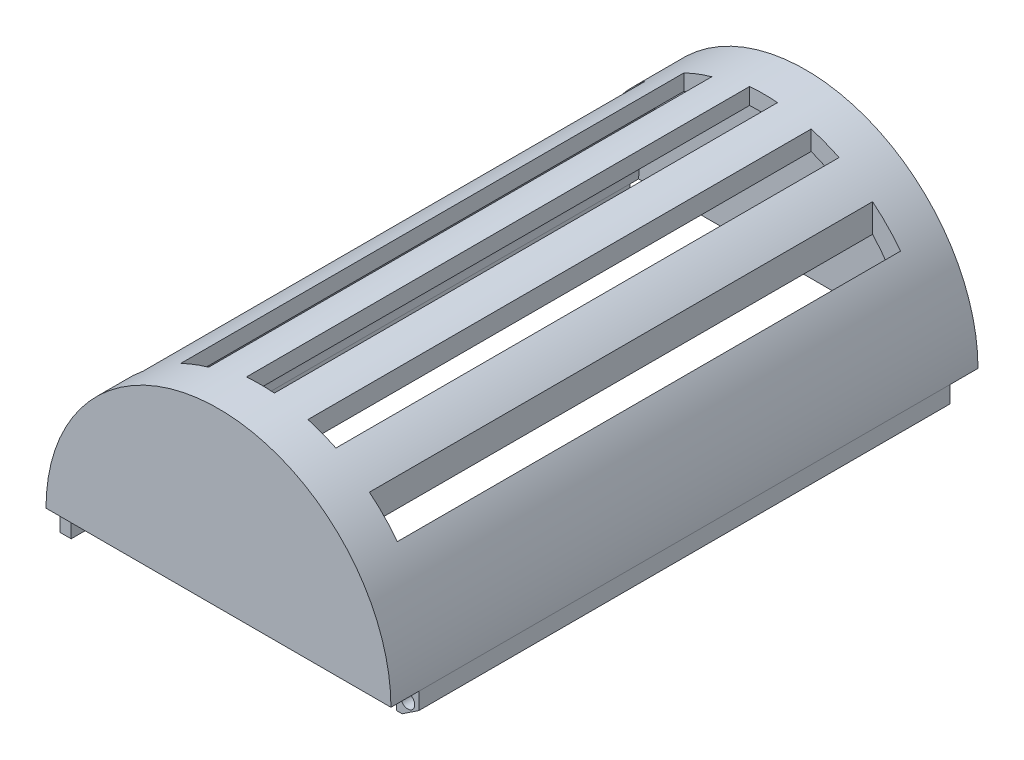
SolidWorks part; units mm, degrees
ref_plane "前基準面" through (0, 0, 0) normal (0, 0, 1) x (1, 0, 0)
ref_plane "上基準面" through (0, 0, 0) normal (0, 1, 0) x (1, 0, 0)
ref_plane "右基準面" through (0, 0, 0) normal (1, 0, 0) x (0, 0, -1)
sketch "草圖1" plane through (0, 0, 0) normal (0, 0, 1) x (1, 0, 0)
  line L0 (-61.7, 0) -> (-57.7, 0) construction
  line L1 (-61.7, 0) -> (-61.7, -10)
  line L2 (-61.7, -10) -> (-57.7, -10)
  line L3 (-57.7, -10) -> (-57.7, 0)
  line L4 (53.7, 0) -> (61.7, 0)
  line L5 (53.7, 0) -> (61.7, 0) construction
  arc A0 (61.7, 0) -> (-61.7, 0) centre (0, 0) ccw
  arc A2 (-57.7, 0) -> (53.7, 0) centre (-2, 0) cw
  dimension "D1" = 111.4
  dimension "D2" = 10
  dimension "D3" = 4
  dimension "D4" = 8
extrude "填料-伸長1" add sketch "草圖1" along normal blind 200
sketch "草圖2" plane through (0, 0, 0) normal (0, 1, 0) x (1, 0, 0)
  line L0 (61.7, 0) -> (-61.7, 0) construction
  line L1 (-5, -10) -> (5, -10)
  line L2 (-5, -10) -> (-5, -190)
  line L3 (-5, -190) -> (5, -190)
  line L4 (5, -10) -> (5, -190)
  line L5 (-5, -10) -> (5, -190) construction
  line L6 (-5, -190) -> (5, -10) construction
  line L7 (17, -10) -> (27, -10)
  line L8 (17, -10) -> (17, -190)
  line L25 (-61.7, -200) -> (61.7, -200) construction
  line L26 (17, -190) -> (27, -190)
  line L27 (27, -10) -> (27, -190)
  line L28 (17, -10) -> (27, -190) construction
  line L29 (17, -190) -> (27, -10) construction
  line L30 (39, -10) -> (49, -10)
  line L31 (39, -10) -> (39, -190)
  line L32 (39, -190) -> (49, -190)
  line L33 (49, -10) -> (49, -190)
  line L34 (39, -10) -> (49, -190) construction
  line L35 (39, -190) -> (49, -10) construction
  line L36 (-26.9439, -11.5695) -> (-16.9439, -11.5695)
  line L37 (-26.9439, -11.5695) -> (-26.9439, -191.5695)
  line L38 (-26.9439, -191.5695) -> (-16.9439, -191.5695)
  line L39 (-16.9439, -11.5695) -> (-16.9439, -191.5695)
  line L40 (-26.9439, -11.5695) -> (-16.9439, -191.5695) construction
  line L41 (-26.9439, -191.5695) -> (-16.9439, -11.5695) construction
  line L42 (-48.8879, -13.139) -> (-38.8879, -13.139)
  line L43 (-48.8879, -13.139) -> (-48.8879, -193.139)
  line L44 (-48.8879, -193.139) -> (-38.8879, -193.139)
  line L45 (-38.8879, -13.139) -> (-38.8879, -193.139)
  line L46 (-48.8879, -13.139) -> (-38.8879, -193.139) construction
  line L47 (-48.8879, -193.139) -> (-38.8879, -13.139) construction
  point P0 (0, -100)
  point P9 (22, -100)
  point P16 (44, -100)
  point P21 (-21.9439, -101.5695)
  point P26 (-43.8879, -103.139)
  dimension "D1" = 10
  dimension "D2" = 10
  dimension "D3" = 10
  dimension "D4" = 3
  dimension "D5" = 3
extrude "除料-伸長1" cut sketch "草圖2" along normal through all
sketch "草圖3" plane through (0, 0, 0) normal (0, -1, 0) x (1, 0, 0)
  line L0 (53.7, 195) -> (61.7, 195)
  line L1 (53.7, 200) -> (53.7, 0) construction
  line L2 (61.7, 200) -> (61.7, 0) construction
  line L3 (61.7, 195) -> (61.7, 5)
  line L4 (61.7, 5) -> (53.7, 5)
  line L5 (53.7, 5) -> (53.7, 195)
  line L6 (53.7, 0) -> (61.7, 0) construction
  line L7 (53.7, 200) -> (61.7, 200) construction
  dimension "D1" = 5
  dimension "D2" = 5
extrude "填料-伸長2" add sketch "草圖3" along normal blind 10
sketch "草圖4" plane through (0, 0, 195) normal (0, 0, 1) x (1, 0, 0)
  line L0 (53.7, 0) -> (61.7, 0) construction
  line L1 (61.7, -10) -> (61.7, 0) construction
  circle A0 centre (57.7, -5) radius 2.5
  dimension "D1" = 5
  dimension "D2" = 5
  dimension "D3" = 4
extrude "除料-伸長2" cut sketch "草圖4" against normal through all
sketch "草圖5" plane through (-61.7, 0, 0) normal (-1, 0, 0) x (0, 0, 1)
  line L0 (90, -10) -> (90, -7)
  line L1 (200, -10) -> (0, -10) construction
  line L2 (90, -7) -> (110, -7)
  line L3 (110, -7) -> (110, -10)
  line L4 (110, -10) -> (90, -10)
  point P4 (100, -10)
  dimension "D1" = 3
  dimension "D2" = 20
extrude "填料-伸長3" add sketch "草圖5" along normal blind 10
sketch "草圖6" plane through (0, 0, 195) normal (0, 0, 1) x (1, 0, 0)
  line L0 (61.7, -10) -> (61.7, -6)
  line L2 (61.7, -6) -> (55.7, -10)
  line L4 (55.7, -10) -> (61.7, -10)
  dimension "D1" = 4
  dimension "D2" = 6
extrude "除料-伸長3" cut sketch "草圖6" against normal through all
sketch "草圖7" plane through (0, 0, 200) normal (0, 0, 1) x (1, 0, 0)
  line L0 (61.7, 0) -> (-61.7, 0)
  arc A0 (-61.7, 0) -> (61.7, 0) centre (0, 0) cw
extrude "填料-伸長4" add sketch "草圖7" along normal blind 5
sketch "草圖8" plane through (0, 0, 0) normal (0, 0, -1) x (-1, 0, 0)
  line L0 (-61.7, 0) -> (61.7, 0)
  arc A0 (-61.7, 0) -> (61.7, 0) centre (0, 0) cw
extrude "填料-伸長5" add sketch "草圖8" along normal blind 5
sketch "草圖9" plane through (0, 0, 0) normal (0, 0, 1) x (1, 0, 0)
  line L0 (-57.7, 0) -> (53.7, 0)
  arc A0 (53.7, 0) -> (-57.7, 0) centre (-2, 0) ccw
extrude "除料-伸長4" cut sketch "草圖9" against normal blind 3
sketch "草圖10" plane through (0, 0, 200) normal (0, 0, -1) x (-1, 0, 0)
  line L0 (-53.7, 0) -> (57.7, 0)
  arc A0 (-53.7, 0) -> (57.7, 0) centre (2, 0) cw
extrude "除料-伸長5" cut sketch "草圖10" against normal blind 3
